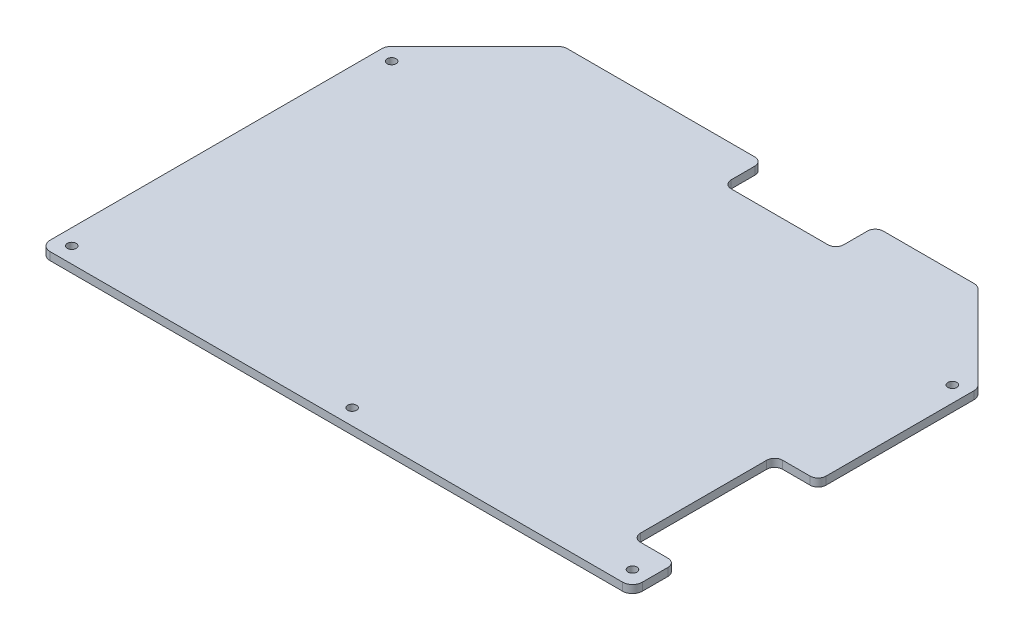
SolidWorks part; units mm, degrees
material "Acier non allié"
ref_plane "Front" through (0, 0, 0) normal (0, 0, 1) x (1, 0, 0)
ref_plane "Top" through (0, 0, 0) normal (0, 1, 0) x (1, 0, 0)
ref_plane "Right" through (0, 0, 0) normal (1, 0, 0) x (0, 0, -1)
sketch "Main scetch" plane through (0, 0, 0) normal (0, 1, 0) x (1, 0, 0)
  line L0 (-150, 0) -> (150, 0)
  line L1 (0, 0) -> (150, 0) construction
  line L2 (0, 0) -> (0, 220) construction
  line L3 (0, 220) -> (150, 220) construction
  line L4 (150, 0) -> (150, 220) construction
  line L5 (150, 0) -> (150, 175)
  line L6 (150, 175) -> (105, 220)
  line L10 (105, 220) -> (-105, 220)
  line L11 (-150, 0) -> (-150, 175)
  line L12 (-150, 175) -> (-105, 220)
  dimension "D1" = 150
  dimension "D2" = 220
  dimension "D3" = 45
  dimension "D4" = 45
extrude "Main extrusion" add sketch "Main scetch" along normal blind 4
fillet "Corner leave" radius 5 6 edges at (-150, 2, 0) (150, 2, -175) (105, 2, -220) (150, 2, 0) (-105, 2, -220) (-150, 2, -175)
sketch "Esquisse1" plane through (0, 4, 0) normal (0, 1, 0) x (1, 0, 0)
  line L0 (-145, 0) -> (145, 0) construction
  line L1 (-150, 172.9289) -> (-150, 5) construction
  line L3 (0, 0) -> (0, 62.3031) construction
  line L4 (150, 5) -> (150, 172.9289) construction
  circle A0 centre (-142, 8) radius 1
  circle A1 centre (-142, 170) radius 1
  circle A4 centre (142, 170) radius 1
  circle A5 centre (142, 8) radius 1
  circle A6 centre (0, 8) radius 1.5
  dimension "D3" = 2
  dimension "D6" = 2
  dimension "D8" = 8
  dimension "D15" = 2
  dimension "D18" = 2
  dimension "D7" = 3
  dimension "D1" = 8
  dimension "D2" = 8
  dimension "D4" = 8
  dimension "D5" = 170
  dimension "D13" = 170
  dimension "D14" = 8
  dimension "D16" = 8
  dimension "D17" = 8
hole_wizard "Dégagement M41" positions "Esquisse2" profile "Esquisse3" hole size "M4" standard "ISO" end condition through all
sketch "Esquisse2" plane through (0, 4, 0) normal (0, 1, 0) x (1, 0, 0)
  point P0 (-142, 8)
  point P3 (-142, 170)
  point P6 (142, 170)
  point P9 (142, 8)
  point P12 (0, 8)
sketch "Esquisse3" plane through (-142, 4, -8) normal (1, 0, 0) x (0, 0, 1)
  line L0 (0, 0) -> (0, 4)
  line L1 (0, 4) -> (2.25, 4)
  line L2 (2.25, 4) -> (2.25, 0)
  line L5 (2.25, 0) -> (0, 0)
  line L11 (0, -6.35) -> (0, 107.95) construction
  dimension "Diamètre du perçage jusqu'au prochain" = 4.5
  dimension "Profondeur du perçage jusqu'au prochain" = 4
sketch "Esquisse4" plane through (0, 4, 0) normal (0, 1, 0) x (1, 0, 0)
  line L0 (150, 5) -> (150, 172.9289) construction
  line L3 (128, 22) -> (150, 22)
  line L5 (-145, 0) -> (145, 0) construction
  line L7 (128, 94) -> (150, 94)
  line L8 (128, 94) -> (128, 22)
  line L10 (150, 94) -> (150, 22)
  dimension "D1" = 22
  dimension "D2" = 72
  dimension "D6" = 22
extrude "Enlèv. mat.-Extru.1" cut sketch "Esquisse4" against normal up to surface (4 mm away) up to face at (-142, 0, -5.75)
sketch "Esquisse5" plane through (0, 4, 0) normal (0, 1, 0) x (1, 0, 0)
  line L0 (150, 94) -> (150, 172.9289) construction
  line L3 (36.3, 200) -> (53, 200)
  line L4 (53, 220) -> (53, 200)
  line L5 (102.9289, 220) -> (-102.9289, 220) construction
  line L7 (-4, 220) -> (53, 220)
  line L8 (-4, 220) -> (-4, 200)
  line L9 (-4, 200) -> (36.3, 200)
  dimension "D1" = 97
  dimension "D2" = 57
  dimension "D5" = 20
extrude "Enlèv. mat.-Extru.2" cut sketch "Esquisse5" against normal up to surface (4 mm away) up to face at (-142, 0, -5.75)
fillet "Congé1" radius 4 8 edges at (53, 2, -220) (-4, 2, -220) (150, 2, -22) (150, 2, -94) (128, 2, -22) (128, 2, -94) (53, 2, -200) (-4, 2, -200)
equation "\"WIDTH\"= 300mm'Total width of the robot"
equation "\"LENGTH\"= 220mm'Total length of the robot"
equation "\"D1@Main scetch\" = \"WIDTH\" / 2"
equation "\"D2@Main scetch\" = \"LENGTH\""
equation "\"CUT_DEPTH\"= 45mm'Depth of the cut on the edges of the plate"
equation "\"D3@Main scetch\" = \"CUT_DEPTH\""
equation "\"D4@Main scetch\" = \"CUT_DEPTH\""
equation "\"Plate_th\"= 3mm'Thickness of the plate"
equation "\"D1\"= \"Plate_th\""
